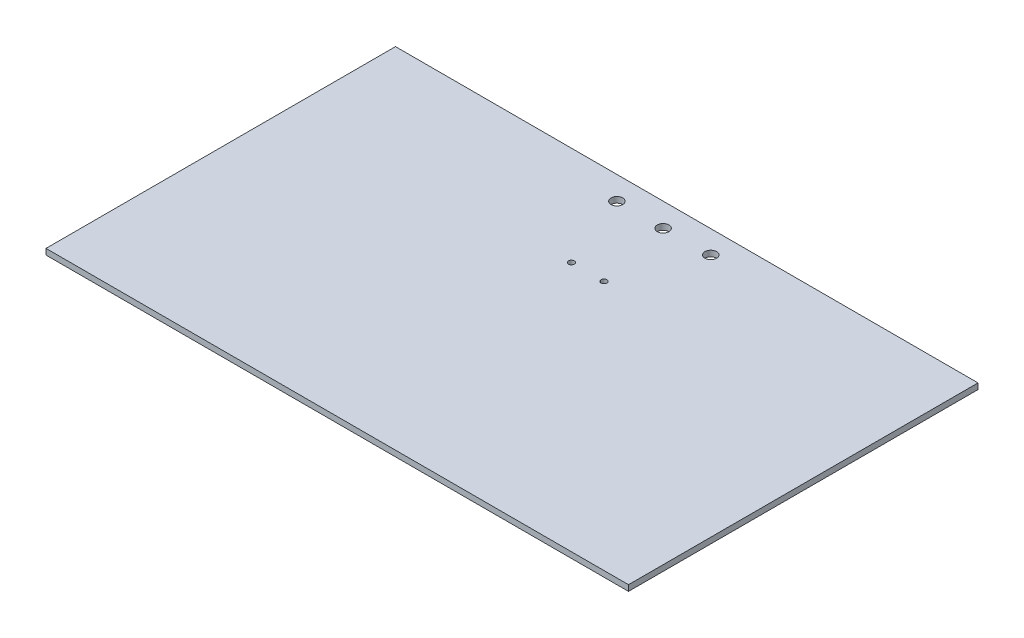
SolidWorks part; units mm, degrees
ref_plane "Front Plane" through (0, 0, 0) normal (0, 0, 1) x (1, 0, 0)
ref_plane "Top Plane" through (0, 0, 0) normal (0, 1, 0) x (1, 0, 0)
ref_plane "Right Plane" through (0, 0, 0) normal (1, 0, 0) x (0, 0, -1)
sketch "Sketch2" plane through (0, 0, 0) normal (0, 1, 0) x (1, 0, 0)
  line L1 (-250, 150) -> (250, 150)
  line L2 (-250, 150) -> (-250, -150)
  line L3 (-250, -150) -> (250, -150)
  line L4 (250, 150) -> (250, -150)
  line L5 (-250, 150) -> (250, -150) construction
  line L6 (-250, -150) -> (250, 150) construction
  point P0 (0, 0)
  dimension "D1" = 500
  dimension "D2" = 300
extrude "Boss-Extrude1" add sketch "Sketch2" along normal blind 5
sketch "Sketch3" plane through (0, 0, 0) normal (0, -1, 0) x (1, 0, 0)
  circle A0 centre (-40.0442, -130.0771) radius 5
  circle A1 centre (-0.0714, -129.778) radius 5
  dimension "D1" = 10
  dimension "D2" = 10
extrude "Cut-Extrude1" cut sketch "Sketch3" against normal through all both and the other way through all
sketch "Sketch4" plane through (0, 5, 0) normal (0, 1, 0) x (1, 0, 0)
  circle A0 centre (40.1964, 130.4485) radius 5
  dimension "D1" = 10
extrude "Cut-Extrude2" cut sketch "Sketch4" against normal through all both and the other way through all
sketch "Sketch5" plane through (0, 5, 0) normal (0, 1, 0) x (1, 0, 0)
  circle A0 centre (14, 65) radius 2.5
  circle A1 centre (-14, 65) radius 2.5
  dimension "D1" = 5
extrude "Cut-Extrude3" cut sketch "Sketch5" against normal through all
